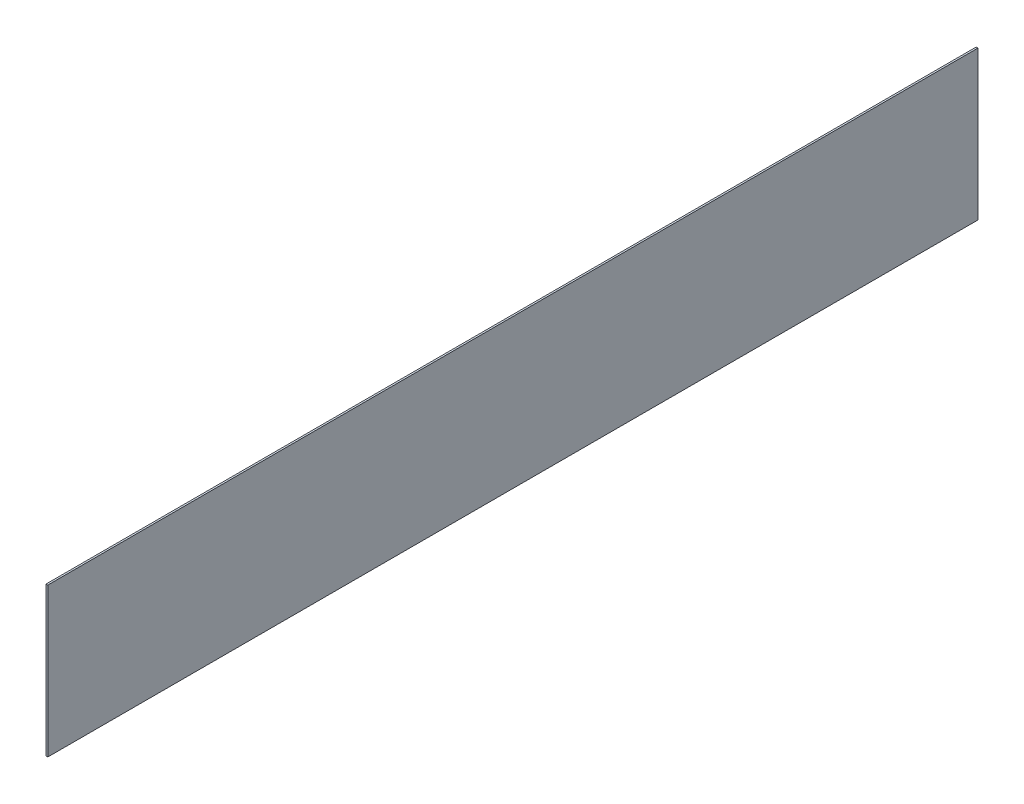
SolidWorks part; units mm, degrees
ref_plane "Front Plane" through (0, 0, 0) normal (0, 0, 1) x (1, 0, 0)
ref_plane "Top Plane" through (0, 0, 0) normal (0, 1, 0) x (1, 0, 0)
ref_plane "Right Plane" through (0, 0, 0) normal (1, 0, 0) x (0, 0, -1)
sketch "Sketch1" plane through (0, 0, 0) normal (1, 0, 0) x (0, 0, -1)
  line L1 (-412.75, -66.0717) -> (412.75, -66.0717)
  line L2 (-412.75, -66.0717) -> (-412.75, 66.0717)
  line L3 (-412.75, 66.0717) -> (412.75, 66.0717)
  line L4 (412.75, -66.0717) -> (412.75, 66.0717)
  line L5 (-412.75, -66.0717) -> (412.75, 66.0717) construction
  line L6 (-412.75, 66.0717) -> (412.75, -66.0717) construction
  point P0 (0, 0)
  dimension "D1" = 132.1435
  dimension "D2" = 825.5
extrude "Boss-Extrude1" add sketch "Sketch1" along normal blind 1.5875
